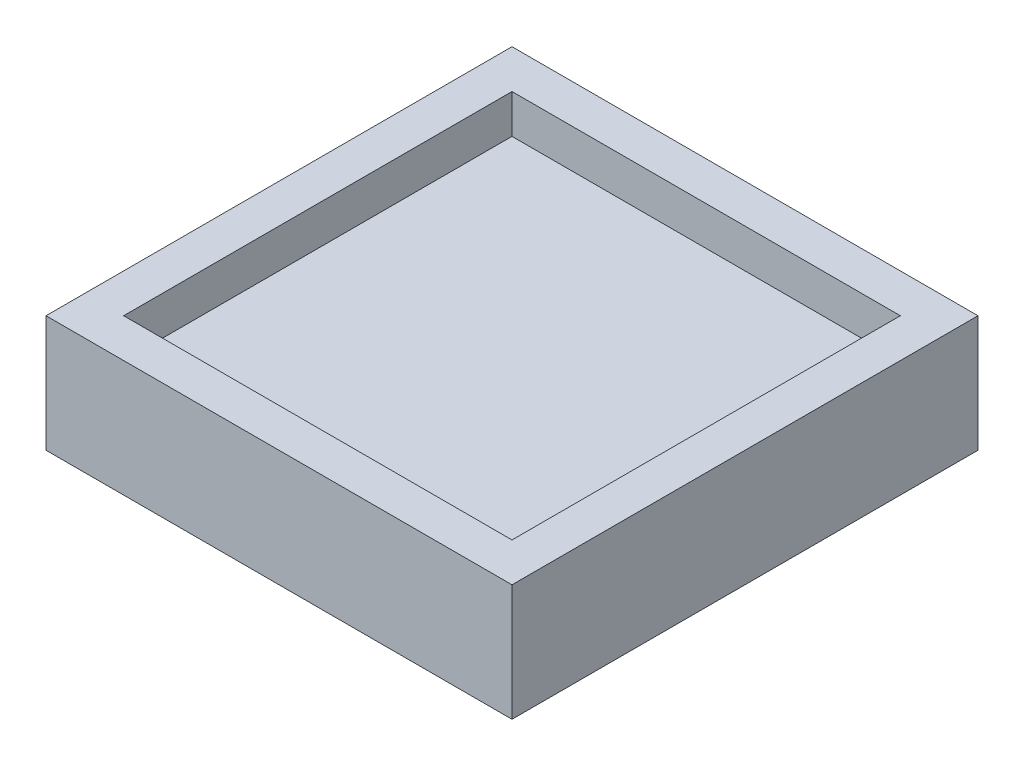
SolidWorks part; units mm, degrees
ref_plane "前视基准面" through (0, 0, 0) normal (0, 0, 1) x (1, 0, 0)
ref_plane "上视基准面" through (0, 0, 0) normal (0, 1, 0) x (1, 0, 0)
ref_plane "右视基准面" through (0, 0, 0) normal (1, 0, 0) x (0, 0, -1)
sketch "草图2" plane through (0, 0, 0) normal (0, 0, 1) x (1, 0, 0)
  line L1 (0, 0) -> (12, 0)
  line L2 (0, 0) -> (0, 3)
  line L3 (0, 3) -> (12, 3)
  line L4 (12, 0) -> (12, 3)
  dimension "D1" = 12
  dimension "D2" = 3
extrude "凸台-拉伸1" add sketch "草图2" along normal blind 12
sketch "草图3" plane through (0, 3, 0) normal (0, 1, 0) x (1, 0, 0)
  line L0 (0, 0) -> (12, -12) construction
  line L1 (12, 0) -> (0, -12) construction
  line L3 (1, -1) -> (11, -1)
  line L4 (1, -1) -> (1, -11)
  line L5 (1, -11) -> (11, -11)
  line L6 (11, -1) -> (11, -11)
  line L7 (1, -1) -> (11, -11) construction
  line L8 (1, -11) -> (11, -1) construction
  point P8 (6, -6)
  dimension "D1" = 10
extrude "切除-拉伸1" cut sketch "草图3" against normal blind 1
